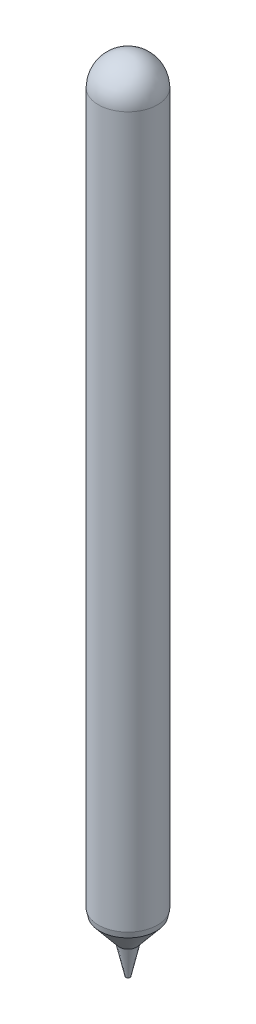
SolidWorks part; units mm, degrees
ref_plane "Front Plane" through (0, 0, 0) normal (0, 0, 1) x (1, 0, 0)
ref_plane "Top Plane" through (0, 0, 0) normal (0, 1, 0) x (1, 0, 0)
ref_plane "Right Plane" through (0, 0, 0) normal (1, 0, 0) x (0, 0, -1)
sketch "Sketch1" plane through (0, 0, 0) normal (0, 0, 1) x (1, 0, 0)
  line L0 (0, 3.9247) -> (0, -126.0753)
  line L1 (0, 8.9247) -> (0, 3.9247)
  line L2 (-5, 3.9247) -> (-5, -116.0753)
  line L3 (-5, -116.0753) -> (-4.7847, -117.0753)
  line L4 (-4.7847, -117.0753) -> (-1.4666, -121.0753)
  line L5 (-1.4666, -121.0753) -> (-1.3996, -121.3752)
  line L6 (-1.3996, -121.3752) -> (-0.35, -126.0753)
  line L7 (-0.35, -126.0753) -> (0, -126.0753)
  arc A0 (0, 8.9247) -> (-5, 3.9247) centre (0, 3.9247) ccw
  point P7 (-0.5, -5.7421)
  point P11 (-0.3792, -6.4357)
  point P12 (-0.2124, -6.6112)
  point P13 (-0.0895, -6.8366)
  point P14 (0, 0)
  point P15 (-3.2776, -123.6756)
  point P16 (0, 0)
  point P17 (-3.3788, -122.9026)
  point P18 (-0.435, -123.7452)
  point P19 (-1.5678, -121.9394)
  point P20 (-1.6078, -120.5703)
  point P21 (-3.4244, -116.2638)
  point P22 (-5, -114.7013)
  point P23 (0, 0)
  point P24 (-4.7847, -117.0753)
  point P25 (-1.3996, -121.3752)
  dimension "D2" = 5
  dimension "D1" = 130
  dimension "D3" = 120
  dimension "D4" = 0.35
  dimension "D6" = 4
revolve "S" add sketch "Sketch1" angle 360 about L0
